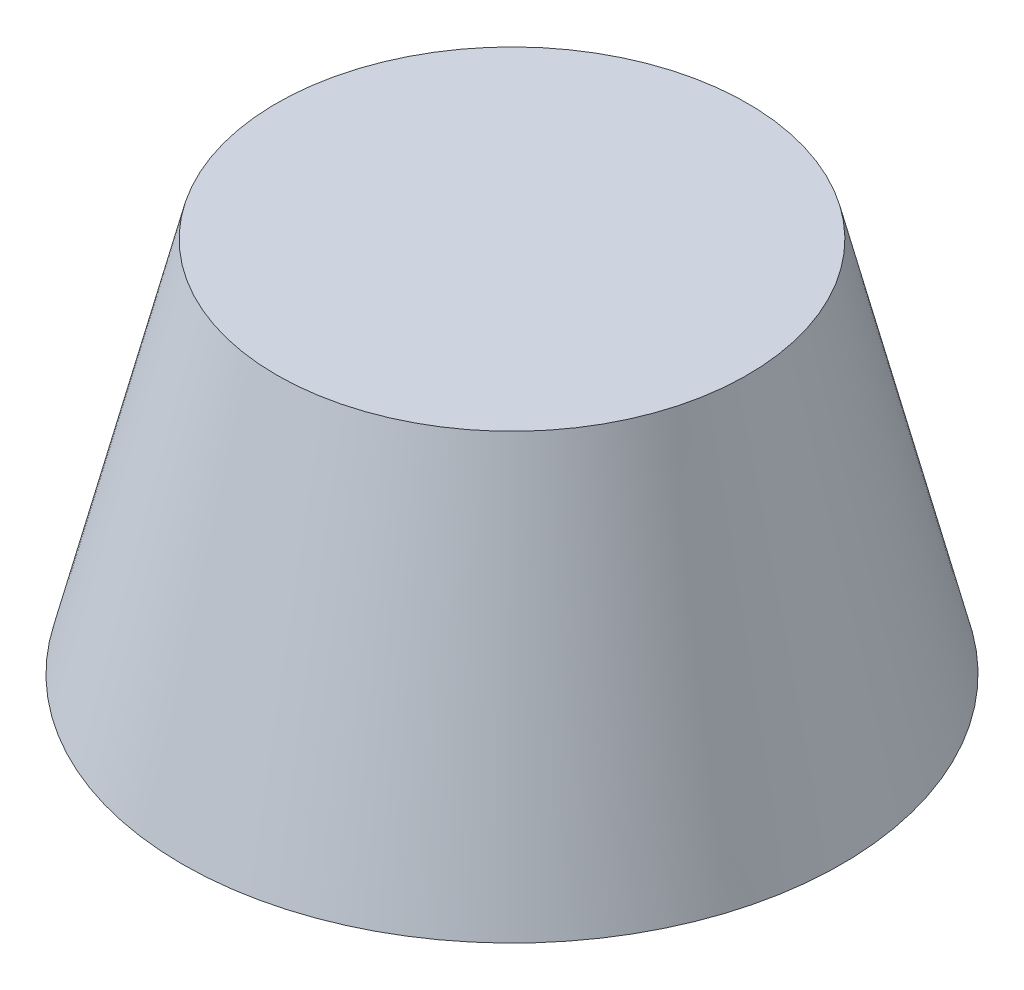
SolidWorks part; units mm, degrees
ref_plane "Front Plane" through (0, 0, 0) normal (0, 0, 1) x (1, 0, 0)
ref_plane "Top Plane" through (0, 0, 0) normal (0, 1, 0) x (1, 0, 0)
ref_plane "Right Plane" through (0, 0, 0) normal (1, 0, 0) x (0, 0, -1)
sketch "Sketch1" plane through (0, 0, 0) normal (0, 1, 0) x (1, 0, 0)
  circle A0 centre (0, 0) radius 22.225
  dimension "D1" = 44.45
ref_plane "Plane1" through (0, 25.4, 0) normal (0, 1, 0) x (1, 0, 0)
sketch "Sketch2" plane through (0, 25.4, 0) normal (0, 1, 0) x (1, 0, 0)
  circle A0 centre (0, 0) radius 15.875
  dimension "D1" = 31.75
loft "Loft1" add profiles "Sketch1", "Sketch2"
sketch "Sketch3" plane through (0, 25.4, 0) normal (0, 1, 0) x (1, 0, 0)
  point P0 (0, 0)
